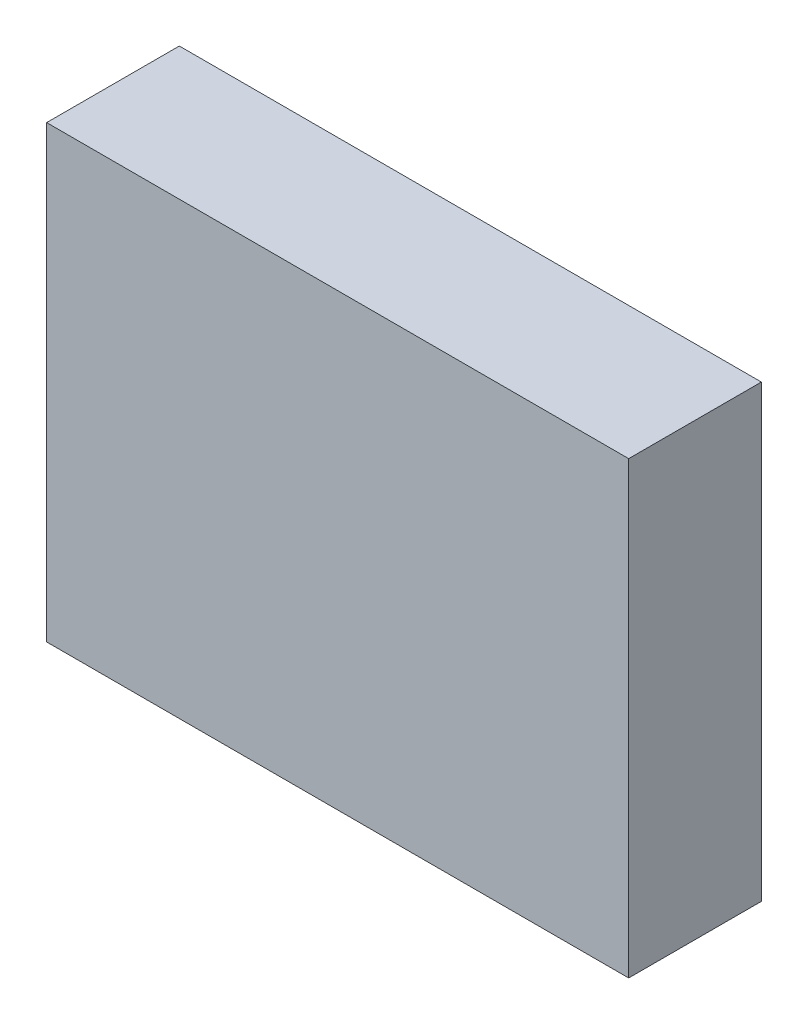
SolidWorks part; units mm, degrees
ref_plane "Front Plane" through (0, 0, 0) normal (0, 0, 1) x (1, 0, 0)
ref_plane "Top Plane" through (0, 0, 0) normal (0, 1, 0) x (1, 0, 0)
ref_plane "Right Plane" through (0, 0, 0) normal (1, 0, 0) x (0, 0, -1)
sketch "Sketch1" plane through (0, 0, 0) normal (0, 0, 1) x (1, 0, 0)
  line L1 (-72.184, 31.6059) -> (-28.31, 31.6059)
  line L2 (-72.184, 31.6059) -> (-72.184, -2.2996)
  line L3 (-72.184, -2.2996) -> (-28.31, -2.2996)
  line L4 (-28.31, 31.6059) -> (-28.31, -2.2996)
extrude "Boss-Extrude1" add sketch "Sketch1" along normal blind 10
